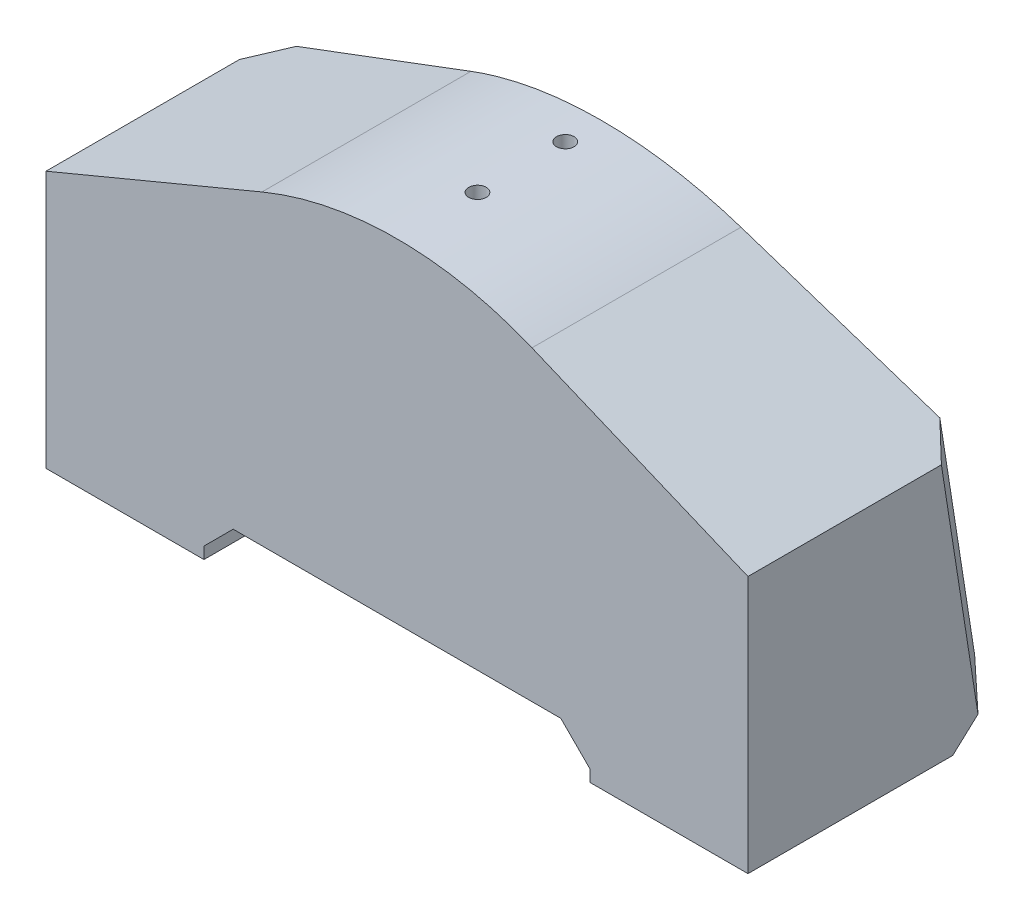
SolidWorks part; units mm, degrees
ref_plane "Alzado" through (0, 0, 0) normal (0, 0, 1) x (1, 0, 0)
ref_plane "Planta" through (0, 0, 0) normal (0, 1, 0) x (1, 0, 0)
ref_plane "Vista lateral" through (0, 0, 0) normal (1, 0, 0) x (0, 0, -1)
sketch "Croquis1" plane through (0, 0, 0) normal (0, 1, 0) x (1, 0, 0)
  line L1 (-60, -22.5) -> (60, -22.5)
  line L2 (-60, -22.5) -> (-60, 22.5)
  line L3 (-60, 22.5) -> (60, 22.5)
  line L4 (60, -22.5) -> (60, 22.5)
  line L5 (-60, -22.5) -> (60, 22.5) construction
  line L6 (-60, 22.5) -> (60, -22.5) construction
  circle A0 centre (-50, -7.5) radius 1.55
  circle A1 centre (50, -7.5) radius 1.55
  point P0 (0, 0)
  dimension "D2" = 10
  dimension "D3" = 15
  dimension "D4" = 10
  dimension "D5" = 15
  dimension "D6" = 3.1
  dimension "D7" = 3.1
  dimension "D1" = 120
  dimension "D8" = 45
extrude "Saliente-Extruir1" add sketch "Croquis1" along normal blind 30
sketch "Croquis2" plane through (0, 30, 0) normal (0, 1, 0) x (1, 0, 0)
  line L1 (-60, -22.5) -> (60, -22.5)
  line L2 (-60, -22.5) -> (-60, 22.5)
  line L3 (-60, 22.5) -> (60, 22.5)
  line L4 (60, -22.5) -> (60, 22.5)
  line L5 (-60, -22.5) -> (60, 22.5) construction
  line L6 (-60, 22.5) -> (60, -22.5) construction
  point P0 (0, 0)
extrude "Saliente-Extruir2" add sketch "Croquis2" against normal blind 44
sketch "Croquis5" plane through (0, 0, 22.5) normal (0, 0, 1) x (1, 0, 0)
  line L2 (-60, 30) -> (-23.0769, 45.3846)
  line L3 (60, 30) -> (23.0769, 45.3846)
  line L4 (-60, 30) -> (60, 30)
  arc A0 (23.0769, 45.3846) -> (-23.0769, 45.3846) centre (0, -10) ccw
  dimension "D2" = 40
extrude "Saliente-Extruir5" add sketch "Croquis5" against normal through all
sketch "Croquis6" plane through (0, -14, 0) normal (0, -1, 0) x (1, 0, 0)
  line L0 (-60, -22.5) -> (-60, 22.5) construction
  line L1 (60, 22.5) -> (60, -22.5) construction
  line L2 (60, -22.5) -> (-60, -22.5) construction
  circle A0 centre (-50, -7.5) radius 1.55
  circle A1 centre (50, -7.5) radius 1.55
  dimension "D1" = 10
  dimension "D2" = 10
  dimension "D3" = 15
  dimension "D4" = 15
  dimension "D5" = 3.1
  dimension "D6" = 3.1
extrude "Cortar-Extruir2" cut sketch "Croquis6" against normal blind 6
sketch "Croquis8" plane through (-60, 0, 0) normal (-1, 0, 0) x (0, 0, 1)
  line L0 (22.5, 50) -> (-12.5, 50)
  line L1 (-22.5, -14) -> (-12.5, 50)
  line L2 (-12.5, 50) -> (-22.5, 50)
  line L3 (-22.5, 50) -> (-22.5, -14)
  line M2 (-22.5, 30) -> (-22.5, -14)
  line M5 (22.5, 30) -> (-22.5, 30)
  dimension "D1" = 35
extrude "Cortar-Extruir3" cut sketch "Croquis8" against normal through all contours L2 L3 L1 M5 | L1 M2 M5
chamfer "Chaflán1" distance 5 angle 45 2 edges at (60, 8, -19.0625) (-60, 8, -19.0625)
sketch "Croquis9" plane through (0, 0, 22.5) normal (0, 0, 1) x (1, 0, 0)
  line L0 (-60, -14) -> (60, -14) construction
  line L2 (-33, -14) -> (-33, -7)
  line L3 (-33, -7) -> (33, -7)
  line L4 (33, -14) -> (33, -7)
  line L5 (0, -14) -> (33, -7) construction
  line L6 (-33, -7) -> (0, -14) construction
  line L7 (-33, -14) -> (33, -14)
  point P0 (0, -14)
  dimension "D1" = 66
  dimension "D2" = 7
extrude "Cortar-Extruir4" cut sketch "Croquis9" against normal through all contours L2 L3 L4 L7
chamfer "Chaflán2" distance 5 angle 45 2 edges at (33, -7, 0.5469) (-33, -7, 0.5469)
sketch "Croquis10" plane through (-60, 0, 0) normal (-1, 0, 0) x (0, 0, 1)
  line L0 (22.5, -14) -> (-12.5, -14) construction
  line L1 (-17.4393, -14) -> (22.5, -14) construction
  line L2 (-12.5, -14) -> (-12.5, -6)
  line L3 (-12.5, -6) -> (-21.25, -6) construction
  line L4 (-22.5, -14) -> (-15.2995, 32.0833) construction
  line L5 (-21.25, -6) -> (-12.5, -14)
  line L6 (-22.5, -14) -> (-21.25, -6)
  line L7 (-22.5, -14) -> (-12.5, -14)
  dimension "D1" = 35
  dimension "D2" = 8
extrude "Cortar-Extruir6" cut sketch "Croquis10" against normal through all contours L7 L6 L5
sketch "Croquis11" plane through (0, -7, 0) normal (0, -1, 0) x (1, 0, 0)
  line L0 (0, -7.75) -> (0, -6.25) construction
  line L2 (0, -6.25) -> (0, 8.75) construction
  line L5 (55, -21.25) -> (-55, -21.25) construction
  circle A1 centre (0, -6.25) radius 1.5
  circle A2 centre (0, 8.75) radius 1.5
  dimension "D2" = 15
  dimension "D3" = 3
  dimension "D1" = 15
  dimension "D4" = 3
extrude "Cortar-Extruir7" cut sketch "Croquis11" against normal through all
